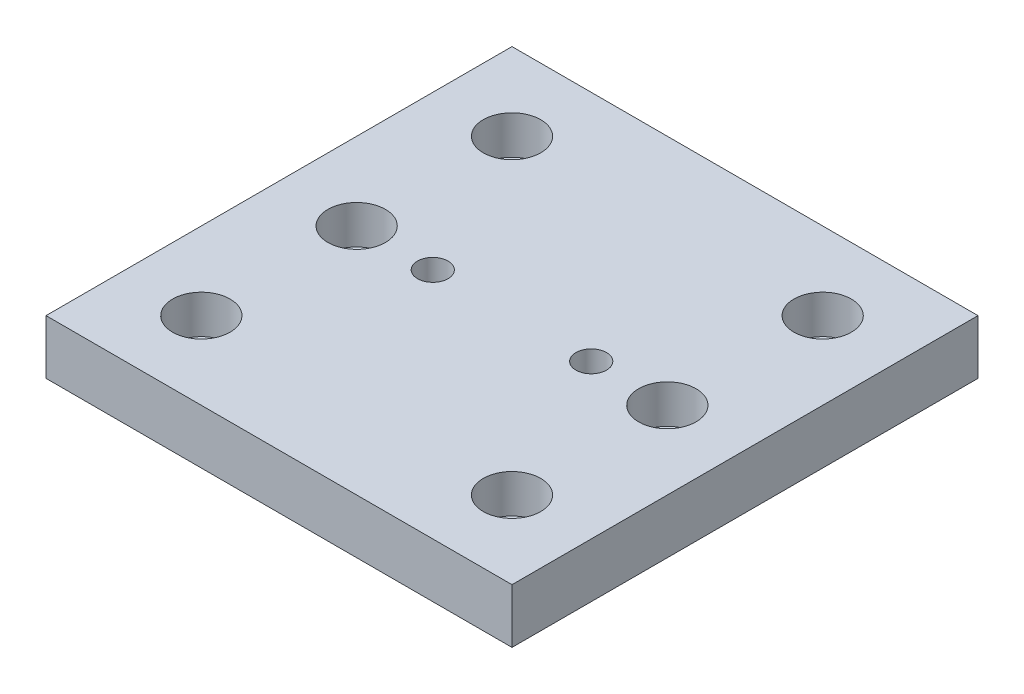
SolidWorks part; units mm, degrees
ref_plane "Front Plane" through (0, 0, 0) normal (0, 0, 1) x (1, 0, 0)
ref_plane "Top Plane" through (0, 0, 0) normal (0, 1, 0) x (1, 0, 0)
ref_plane "Right Plane" through (0, 0, 0) normal (1, 0, 0) x (0, 0, -1)
sketch "Sketch1" plane through (0, 0, 0) normal (0, 1, 0) x (1, 0, 0)
  line L1 (-38.1, 38.1) -> (38.1, 38.1)
  line L2 (-38.1, 38.1) -> (-38.1, -38.1)
  line L3 (-38.1, -38.1) -> (38.1, -38.1)
  line L4 (38.1, 38.1) -> (38.1, -38.1)
  point P4 (0, 38.1)
  point P5 (38.1, 0)
  point P6 (30.7983, -17.878)
  dimension "D1" = 76.2
  dimension "D2" = 76.2
  dimension "D3" = 38.1
  dimension "D4" = 38.1
extrude "Boss-Extrude1" add sketch "Sketch1" along normal blind 8.89
hole_wizard "Tap Drill for M6x1.0 Tap1" positions "Sketch2" profile "Sketch3" hole size "M6x1.0" standard "ANSI Metric"
sketch "Sketch2" plane through (0, 8.89, 0) normal (0, 1, 0) x (1, 0, 0)
  line L0 (38.1, 38.1) -> (-38.1, 38.1) construction
  line L1 (-38.1, -38.1) -> (38.1, -38.1) construction
  point P0 (-12.954, 0)
  point P2 (12.954, 0)
  point P4 (0, 0)
  dimension "D1" = 25.908
  dimension "D2" = 12.954
  dimension "D3" = 38.1
  dimension "D4" = 38.1
sketch "Sketch3" plane through (-12.954, 8.89, 0) normal (1, 0, 0) x (0, 0, 1)
  line L0 (0, 0) -> (0, 10.3922)
  line L1 (0, 10.3922) -> (2.5, 8.89)
  line L2 (2.5, 8.89) -> (2.5, 0)
  line L5 (2.5, 0) -> (0, 0)
  line L10 (0, 10.3922) -> (-2.5, 8.89) construction
  line L11 (0, -6.35) -> (0, 107.95) construction
  dimension "Hole Dia." = 5
  dimension "Hole Depth" = 8.89
  dimension "Drill Angle" = 118
hole_wizard "CBORE for M6 SHCS1" positions "Sketch4" profile "Sketch5" counterbore size "M6" standard "ANSI Metric"
sketch "Sketch4" plane through (0, 8.89, 0) normal (0, 1, 0) x (1, 0, 0)
  line L4 (38.1, 38.1) -> (-38.1, 38.1) construction
  line L5 (-38.1, 38.1) -> (-38.1, -38.1) construction
  line L6 (38.1, -38.1) -> (38.1, 38.1) construction
  point P0 (-25.4, 25.4)
  point P2 (25.4, 25.4)
  point P4 (25.4, -25.4)
  point P6 (-25.4, -25.4)
  point P8 (-25.4, 0)
  point P10 (25.4, 0)
  point P13 (0, 0)
  point P14 (0, 0)
  point P23 (0, 0)
  dimension "D1" = 25.4
  dimension "D2" = 25.4
  dimension "D3" = 25.4
  dimension "D4" = 25.4
  dimension "D5" = 50.8
  dimension "D6" = 50.8
  dimension "D7" = 12.7
  dimension "D8" = 12.7
  dimension "D9" = 12.7
  dimension "D10" = 12.7
  dimension "D11" = 12.7
  dimension "D12" = 12.7
sketch "Sketch5" plane through (-25.4, 8.89, -25.4) normal (1, 0, 0) x (0, 0, 1)
  line L0 (0, 0) -> (0, 10.8728)
  line L1 (0, 10.8728) -> (3.3, 8.89)
  line L2 (3.3, 8.89) -> (3.3, 6.3)
  line L3 (3.3, 6.3) -> (4.7, 6.3)
  line L4 (4.7, 6.3) -> (4.7, 0)
  line L5 (4.7, 0) -> (0, 0)
  line L10 (0, 10.8728) -> (-3.3, 8.89) construction
  line L11 (0, -6.35) -> (0, 107.95) construction
  dimension "Hole Dia." = 6.6
  dimension "Hole Depth" = 8.89
  dimension "C'Bore Dia." = 9.4
  dimension "C'Bore Depth" = 6.3
  dimension "Drill Angle" = 118
